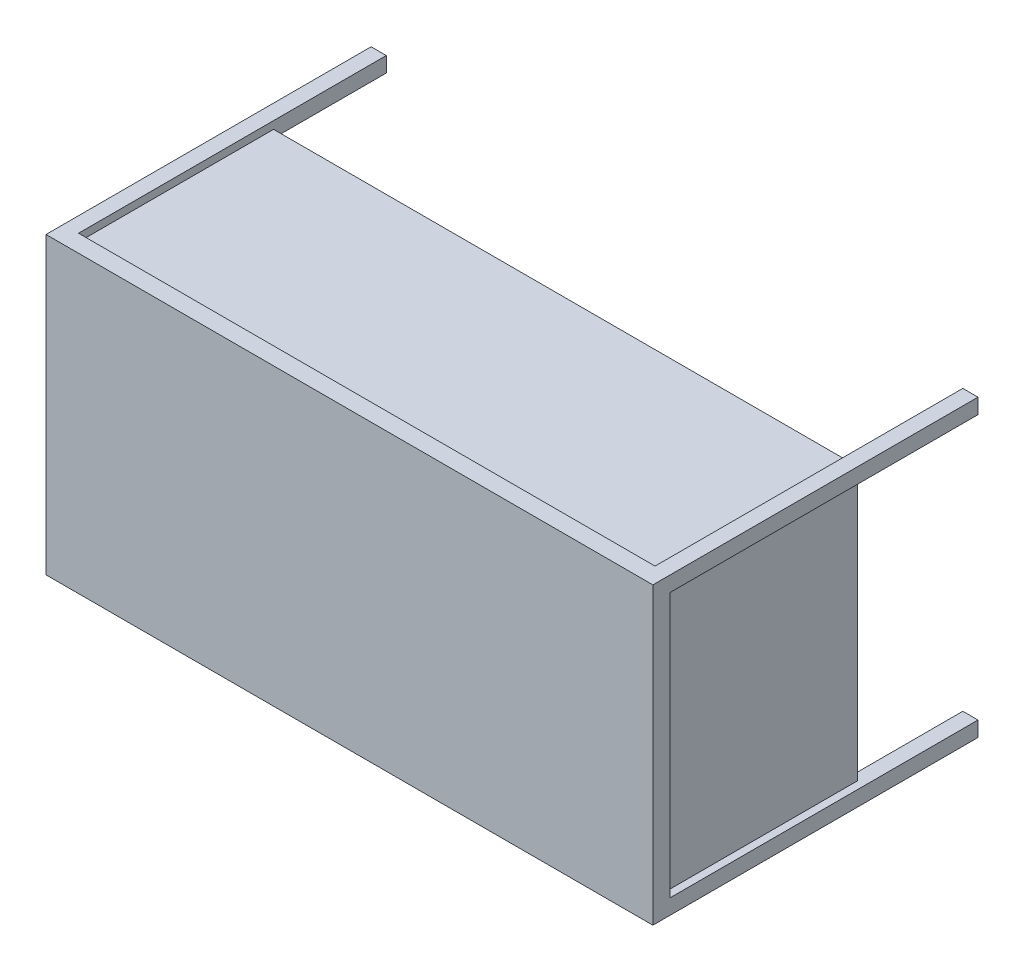
SolidWorks part; units mm, degrees
material "1060 Legierung"
ref_plane "Ebene vorne" through (0, 0, 0) normal (0, 0, 1) x (1, 0, 0)
ref_plane "Ebene oben" through (0, 0, 0) normal (0, 1, 0) x (1, 0, 0)
ref_plane "Ebene rechts" through (0, 0, 0) normal (1, 0, 0) x (0, 0, -1)
sketch "Skizze1" plane through (0, 0, 0) normal (0, 0, 1) x (1, 0, 0)
  line L1 (-20.4314, 9.7901) -> (1379.5686, 9.7901)
  line L2 (-20.4314, 9.7901) -> (-20.4314, -670.2099)
  line L3 (-20.4314, -670.2099) -> (1379.5686, -670.2099)
  line L4 (1379.5686, 9.7901) -> (1379.5686, -670.2099)
  dimension "D1" = 1400
  dimension "D2" = 680
extrude "Aufsatz-Linear austragen1" add sketch "Skizze1" along normal blind 40
sketch "Skizze2" plane through (0, 0, 0) normal (0, 0, -1) x (-1, 0, 0)
  line L1 (-1379.5686, 9.7901) -> (-1344.5686, 9.7901)
  line L2 (-1379.5686, 9.7901) -> (-1379.5686, -25.2099)
  line L3 (-1379.5686, -25.2099) -> (-1344.5686, -25.2099)
  line L4 (-1344.5686, 9.7901) -> (-1344.5686, -25.2099)
  line L5 (-1379.5686, -670.2099) -> (-1344.5686, -670.2099)
  line L6 (-1379.5686, -670.2099) -> (-1379.5686, -635.2099)
  line L7 (-1379.5686, -635.2099) -> (-1344.5686, -635.2099)
  line L8 (-1344.5686, -670.2099) -> (-1344.5686, -635.2099)
  line L9 (20.4314, 9.7901) -> (-14.5686, 9.7901)
  line L10 (20.4314, 9.7901) -> (20.4314, -25.2099)
  line L11 (20.4314, -25.2099) -> (-14.5686, -25.2099)
  line L12 (-14.5686, 9.7901) -> (-14.5686, -25.2099)
  line L13 (20.4314, -670.2099) -> (-14.5686, -670.2099)
  line L14 (20.4314, -670.2099) -> (20.4314, -635.2099)
  line L15 (20.4314, -635.2099) -> (-14.5686, -635.2099)
  line L16 (-14.5686, -670.2099) -> (-14.5686, -635.2099)
  point P20 (20.4314, -652.7099)
  dimension "D1" = 35
  dimension "D2" = 35
  dimension "D3" = 35
  dimension "D4" = 35
  dimension "D5" = 35
  dimension "D6" = 35
  dimension "D7" = 35
  dimension "D8" = 35
extrude "Aufsatz-Linear austragen2" add sketch "Skizze2" along normal blind 710
sketch "Skizze3" plane through (0, 0, 0) normal (0, 0, -1) x (-1, 0, 0)
  line L0 (-1344.5686, -7.7099) -> (-1379.5686, -7.7099) construction
  line L1 (-1344.5686, -25.2099) -> (-1344.5686, 9.7901) construction
  line L2 (-1379.5686, 9.7901) -> (-1379.5686, -25.2099) construction
  line L3 (-1362.0686, -25.2099) -> (-1362.0686, 9.7901) construction
  line L4 (-1379.5686, -25.2099) -> (-1344.5686, -25.2099) construction
  line L5 (-1344.5686, 9.7901) -> (-1379.5686, 9.7901) construction
  line L6 (2.9314, -635.2099) -> (2.9314, -670.2099) construction
  line L7 (20.4314, -635.2099) -> (-14.5686, -635.2099) construction
  line L8 (-14.5686, -670.2099) -> (20.4314, -670.2099) construction
  line L9 (20.4314, -652.7099) -> (-14.5686, -652.7099) construction
  line L10 (20.4314, -670.2099) -> (20.4314, -635.2099) construction
  line L11 (-14.5686, -635.2099) -> (-14.5686, -670.2099) construction
  line L13 (2.9314, -652.7099) -> (-1362.0686, -652.7099)
  line L14 (2.9314, -652.7099) -> (2.9314, -7.7099)
  line L15 (2.9314, -7.7099) -> (-1362.0686, -7.7099)
  line L16 (-1362.0686, -652.7099) -> (-1362.0686, -7.7099)
extrude "Aufsatz-Linear austragen3" add sketch "Skizze3" along normal blind 450
